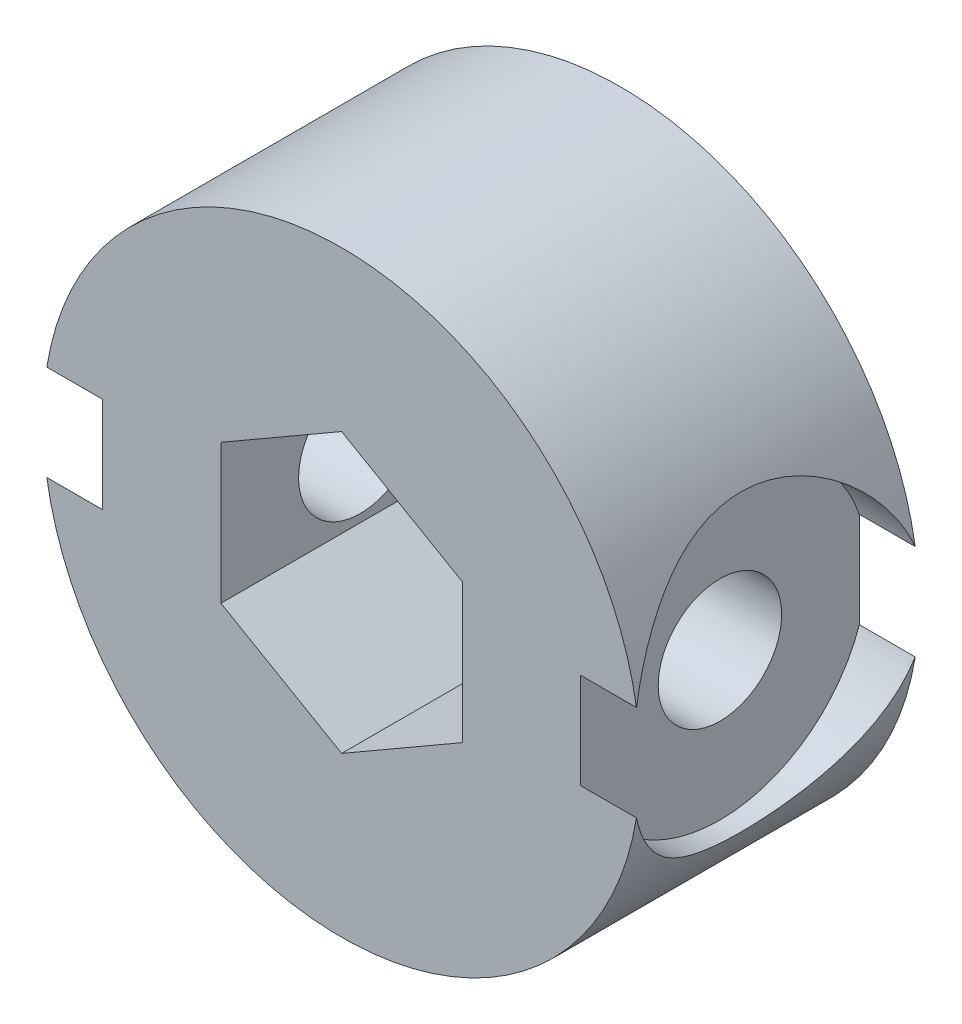
SolidWorks part; units mm, degrees
ref_plane "Front Plane" through (0, 0, 0) normal (0, 0, 1) x (1, 0, 0)
ref_plane "Top Plane" through (0, 0, 0) normal (0, 1, 0) x (1, 0, 0)
ref_plane "Right Plane" through (0, 0, 0) normal (1, 0, 0) x (0, 0, -1)
sketch "Sketch1" plane through (0, 0, 0) normal (0, 0, 1) x (1, 0, 0)
  line L2 (-3.0311, 1.75) -> (0, 3.5)
  line L3 (0, 3.5) -> (3.0311, 1.75)
  line L4 (3.0311, 1.75) -> (3.0311, -1.75)
  line L5 (3.0311, -1.75) -> (0, -3.5)
  line L6 (0, -3.5) -> (-3.0311, -1.75)
  line L7 (-3.0311, -1.75) -> (-3.0311, 1.75)
  circle A0 centre (0, 0) radius 7.5
  point P7 (0, 0)
  point P10 (0, 0)
extrude "Boss-Extrude2" add sketch "Sketch1" along normal blind 7
ref_plane "Plane1" through (0, 0, 0) normal (-1, 0, 0) x (0, 0, 1)
sketch "Sketch2" plane through (0, 0, 0) normal (-1, 0, 0) x (0, 0, 1)
  line L0 (0, 0) -> (7, 0) construction
  line L1 (7, -7.5) -> (7, 7.5) construction
  circle A0 centre (3.5, 0) radius 1.55
extrude "Cut-Extrude1" cut sketch "Sketch2" against normal blind 7.5 and the other way blind 7.5
ref_plane "Plane2" through (-6, 0, 0) normal (-1, 0, 0) x (0, 0, 1)
ref_plane "Plane3" through (6, 0, 0) normal (-1, 0, 0) x (0, 0, 1)
sketch "Sketch4" plane through (-6, 0, 0) normal (-1, 0, 0) x (0, 0, 1)
  circle A0 centre (3.5, 0) radius 3.7
extrude "Cut-Extrude2" cut sketch "Sketch4" along normal blind 4
sketch "Sketch5" plane through (6, 0, 0) normal (-1, 0, 0) x (0, 0, 1)
  circle A0 centre (3.5, 0) radius 3.7
extrude "Cut-Extrude3" cut sketch "Sketch5" against normal blind 4
